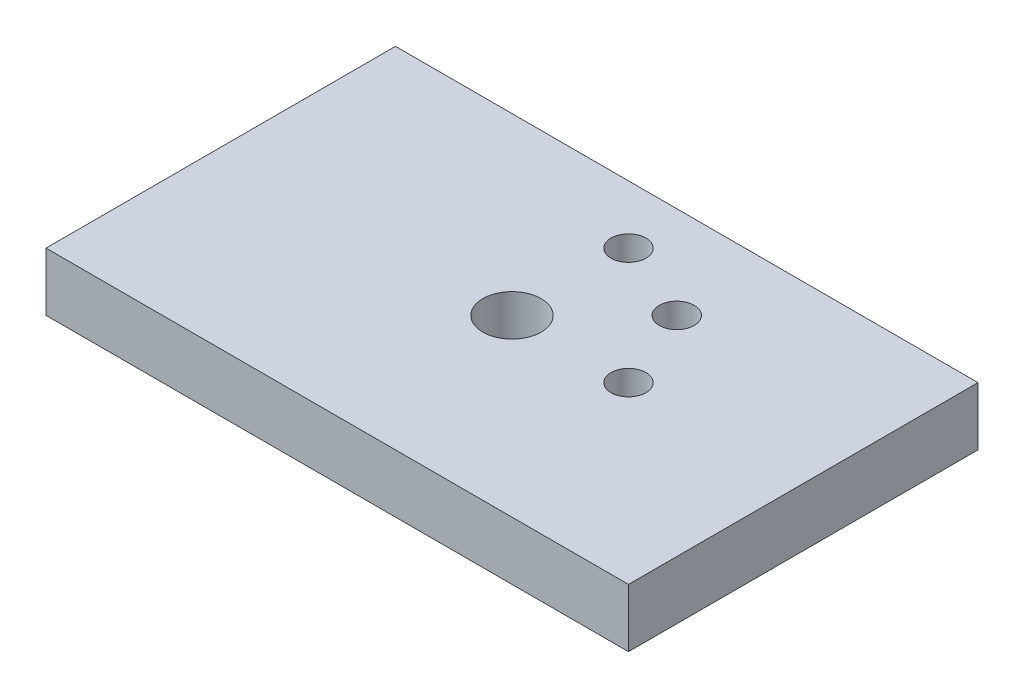
SolidWorks part; units mm, degrees
ref_plane "前视基准面" through (0, 0, 0) normal (0, 0, 1) x (1, 0, 0)
ref_plane "上视基准面" through (0, 0, 0) normal (0, 1, 0) x (1, 0, 0)
ref_plane "右视基准面" through (0, 0, 0) normal (1, 0, 0) x (0, 0, -1)
other "Configuration Table"
sketch "草图1" plane through (0, 0, 0) normal (0, 1, 0) x (1, 0, 0)
  line L1 (-50, -30) -> (50, -30)
  line L2 (-50, -30) -> (-50, 30)
  line L3 (-50, 30) -> (50, 30)
  line L4 (50, -30) -> (50, 30)
  line L5 (0, 30) -> (0, -30) construction
  line L6 (-50, 0) -> (50, 0) construction
  point P0 (0, 0)
extrude "凸台-拉伸1" add sketch "草图1" along normal blind 10
sketch "草图2" plane through (0, 0, 0) normal (0, 1, 0) x (1, 0, 0)
  circle A0 centre (0, 0) radius 5
extrude "切除-拉伸1" cut sketch "草图2" along normal blind 20
sketch "草图3" plane through (0, 0, 0) normal (0, 1, 0) x (1, 0, 0)
  circle A0 centre (20, 0) radius 3
extrude "切除-拉伸2" cut sketch "草图3" along normal blind 20
pattern_circular "阵列(圆周)1" count 3 over 90 about axis through (0, 0, 0) along (0, 1, 0) of "切除-拉伸2"
